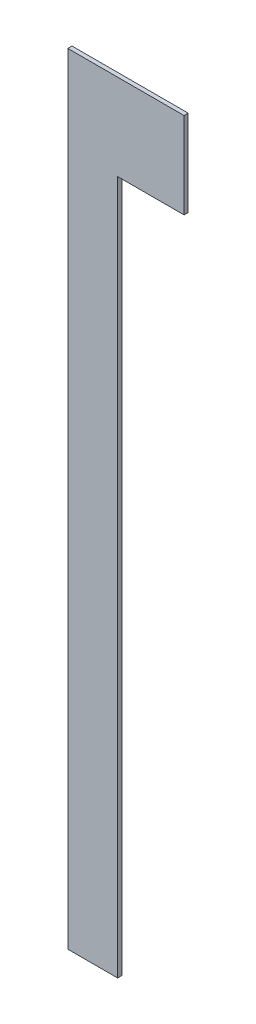
SolidWorks part; units mm, degrees
material "Гипс"
ref_plane "Спереди" through (0, 0, 0) normal (0, 0, 1) x (1, 0, 0)
ref_plane "Сверху" through (0, 0, 0) normal (0, 1, 0) x (1, 0, 0)
ref_plane "Справа" through (0, 0, 0) normal (1, 0, 0) x (0, 0, -1)
sketch "Эскиз1" plane through (0, 0, 0) normal (0, 0, 1) x (1, 0, 0)
  line L0 (150, -260) -> (950, -260) construction
  line L1 (350, -0.75) -> (0, -0.75)
  line L2 (350, -0.75) -> (350, -260)
  line L4 (0, -0.75) -> (0, -2350)
  line L5 (150, -260) -> (350, -260)
  line L6 (150, -2350) -> (150, -260) construction
  line L7 (150, -2350) -> (150, -260)
  line L8 (150, -2350) -> (0, -2350)
extrude "Бобышка-Вытянуть1" add sketch "Эскиз1" against normal blind 12.5
